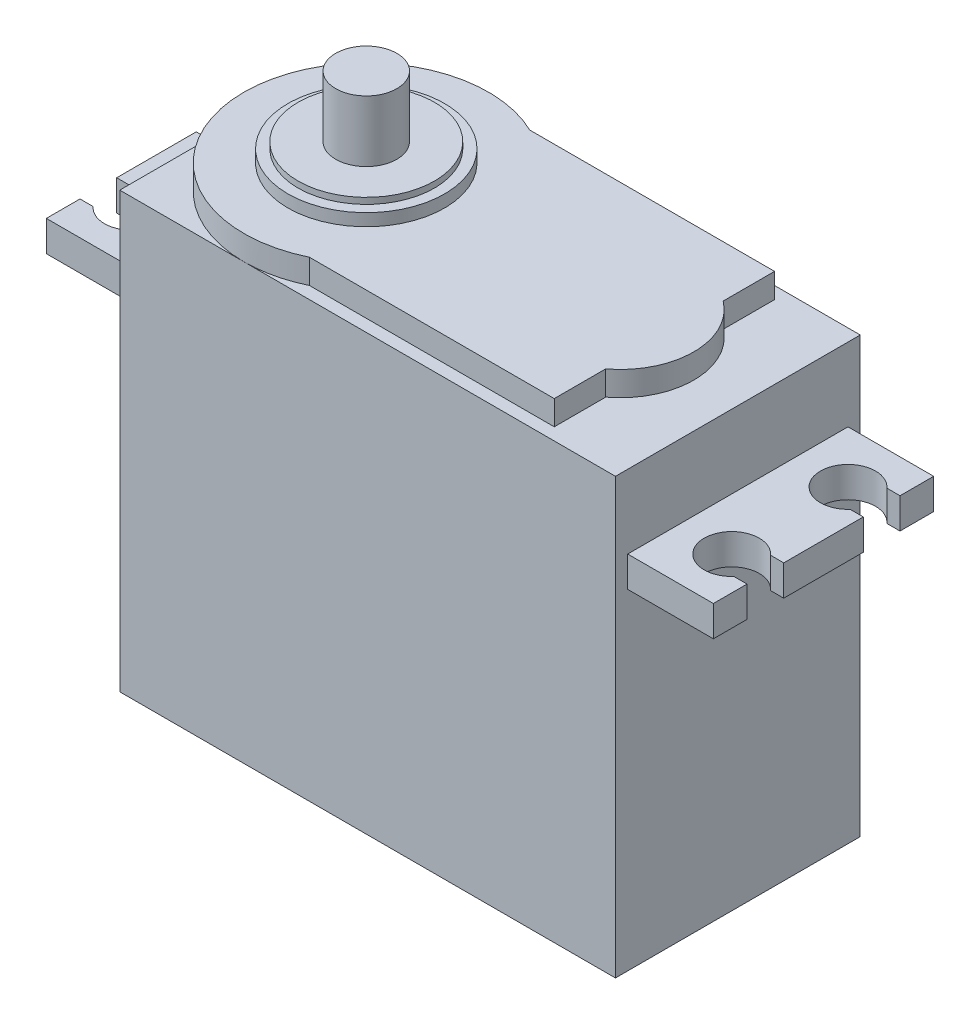
SolidWorks part; units mm, degrees
ref_plane "Front" through (0, 0, 0) normal (0, 0, 1) x (1, 0, 0)
ref_plane "Top" through (0, 0, 0) normal (0, 1, 0) x (1, 0, 0)
ref_plane "Right" through (0, 0, 0) normal (1, 0, 0) x (0, 0, -1)
sketch "Sketch1" plane through (0, 0, 0) normal (0, 1, 0) x (1, 0, 0)
  line L0 (-20.25, 10) -> (20.25, -10) construction
  line L1 (-20.25, -10) -> (20.25, -10)
  line L2 (-20.25, -10) -> (-20.25, 10)
  line L3 (-20.25, 10) -> (20.25, 10)
  line L4 (20.25, -10) -> (20.25, 10)
  line L5 (20.25, 10) -> (-20.25, -10) construction
  dimension "D1" = 20
  dimension "D2" = 40.5
extrude "Boss-Extrude1" add sketch "Sketch1" along normal blind 35.5
sketch "Sketch2" plane through (0, 35.5, 0) normal (0, 1, 0) x (1, 0, 0)
  line L0 (-5.75, -9) -> (14.25, -9)
  line L1 (14.25, -9) -> (14.25, -4.8)
  line L2 (-5.75, 9) -> (14.25, 9)
  line L3 (14.25, 9) -> (14.25, 4.8)
  line L4 (20.25, 10) -> (-20.25, 10) construction
  line L5 (-20.25, -10) -> (20.25, -10) construction
  line L6 (20.25, -10) -> (20.25, 10) construction
  line L7 (20.25, -10) -> (20.25, 10) construction
  arc A0 (-5.75, 9) -> (-5.75, -9) centre (-10.1089, 0) ccw
  arc A1 (14.25, 4.8) -> (14.25, -4.8) centre (10.65, 0) cw
  point P6 (0, 10)
  point P12 (16.65, 0)
  point P13 (20.25, 0)
  dimension "D1" = 1
  dimension "D3" = 4.2
  dimension "D2" = 1
  dimension "D4" = 3.6
  dimension "D5" = 20
  dimension "D6" = 6
extrude "Boss-Extrude2" add sketch "Sketch2" along normal blind 2
sketch "Sketch3" plane through (0, 37.5, 0) normal (0, 1, 0) x (1, 0, 0)
  circle A0 centre (-10.1089, 0) radius 6.4
  arc A1 (-10.1089, 10) -> (-10.1089, -10) centre (-10.1089, 0) ccw construction
  dimension "D1" = 12.8
extrude "Boss-Extrude3" add sketch "Sketch3" along normal blind 1
sketch "Sketch4" plane through (0, 38.5, 0) normal (0, 1, 0) x (1, 0, 0)
  circle A0 centre (-10.1089, 0) radius 5.575
  circle A1 centre (-10.1089, 0) radius 6.4 construction
  dimension "D1" = 11.15
extrude "Boss-Extrude4" add sketch "Sketch4" along normal blind 0.5
ref_plane "Plane1" through (0, 29.5, 0) normal (0, 1, 0) x (1, 0, 0)
sketch "Sketch5" plane through (0, 29.5, 0) normal (0, 1, 0) x (1, 0, 0)
  line L0 (20.25, 9) -> (27.25, 9)
  line L1 (20.25, -10) -> (20.25, 10) construction
  line L2 (27.25, 0) -> (27.25, 3.25)
  line L3 (20.25, 0) -> (27.25, 0)
  line L4 (20.25, 0) -> (20.25, 9)
  line L5 (20.25, 10) -> (-10.1089, 10) construction
  line L7 (24.5, 7) -> (24.5, 9) construction
  line L8 (27.25, 6.25) -> (27.25, 9)
  line L9 (26.1771, 6.25) -> (27.25, 6.25)
  line L10 (26.1771, 3.25) -> (27.25, 3.25)
  arc A0 (26.1771, 6.25) -> (26.1771, 3.25) centre (24.5, 4.75) ccw
  point P9 (22.25, 4.75)
  dimension "D4" = 4.5
  dimension "D5" = 2
  dimension "D1" = 1
  dimension "D2" = 9
  dimension "D3" = 7
  dimension "D6" = 3
  dimension "D7" = 2
extrude "Boss-Extrude5" add sketch "Sketch5" against normal blind 2.5
mirror "Mirror1" about plane through (0, 0, 0) normal (1, 0, 0) of "Boss-Extrude5"
mirror "Mirror2" about plane through (0, 0, 0) normal (0, 0, 1) of "Boss-Extrude5", "Mirror1"
sketch "Sketch6" plane through (0, 39, 0) normal (0, 1, 0) x (1, 0, 0)
  circle A0 centre (-10.1089, 0) radius 2.5
  dimension "D1" = 5
extrude "Boss-Extrude6" add sketch "Sketch6" along normal blind 5
